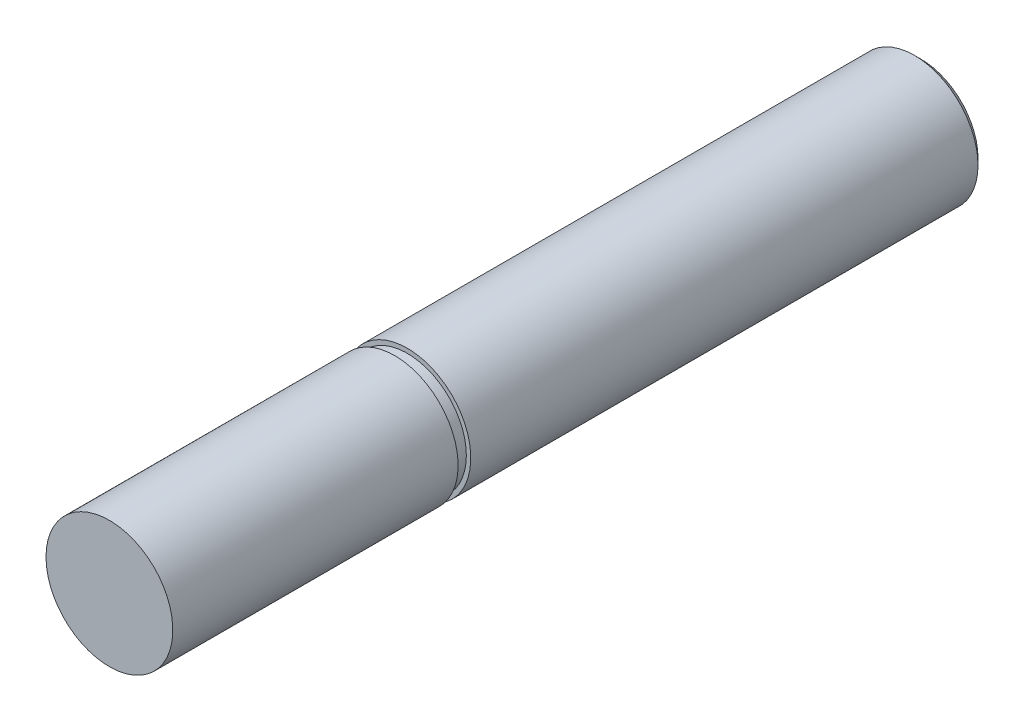
SolidWorks part; units mm, degrees
ref_plane "前视基准面" through (0, 0, 0) normal (0, 0, 1) x (1, 0, 0)
ref_plane "上视基准面" through (0, 0, 0) normal (0, 1, 0) x (1, 0, 0)
ref_plane "右视基准面" through (0, 0, 0) normal (1, 0, 0) x (0, 0, -1)
sketch "草图1" plane through (0, 0, 0) normal (0, 0, 1) x (1, 0, 0)
  circle A0 centre (0, 0) radius 5
  dimension "D1" = 10
extrude "拉伸1" add sketch "草图1" along normal blind 104
sketch "草图2" plane through (0, 0, 0) normal (0, 1, 0) x (1, 0, 0)
  line L0 (12.5, -41.5) -> (-12.5, -41.5) construction
  line L1 (4.65, -41.5) -> (8.1489, -41.5)
  line L2 (4.65, -41.5) -> (4.65, -40.5)
  line L3 (4.65, -40.5) -> (8.1489, -40.5)
  line L4 (8.1489, -41.5) -> (8.1489, -40.5)
  line L5 (5, -104) -> (5, 0) construction
  dimension "D1" = 1
  dimension "D2" = 0.35
revolve "切除-旋转1" cut sketch "草图2" angle 360 about axis through (0, 0, 104) along (0, 0, -1)
chamfer "倒角1" distance 0.5 angle 45 1 edges at (5, 0, 0)
sketch "草图4" plane through (0, 0, 0) normal (0, 1, 0) x (1, 0, 0)
  line L1 (-15.3108, -116.9812) -> (29.1821, -116.9812)
  line L2 (-15.3108, -116.9812) -> (-15.3108, -64)
  line L3 (-15.3108, -64) -> (29.1821, -64)
  line L4 (29.1821, -116.9812) -> (29.1821, -64)
  line L5 (-4.5, -104) -> (4.5, -104) construction
  dimension "D1" = 40
extrude "拉伸2" cut sketch "草图4" against normal mid plane 10
